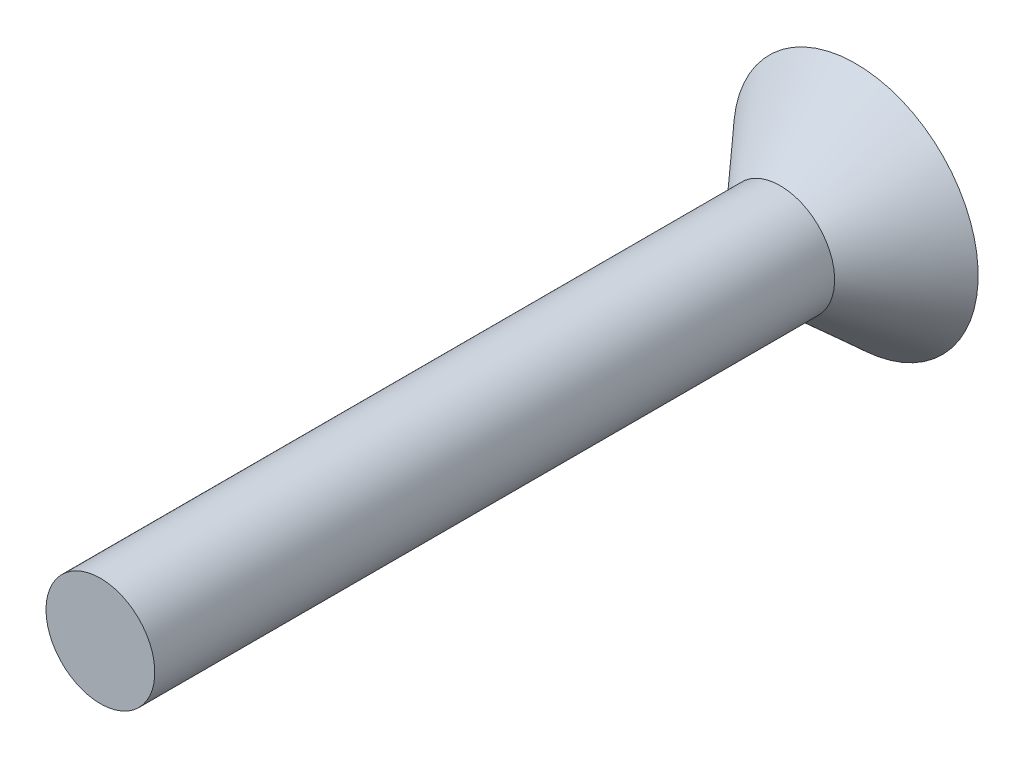
SolidWorks part; units mm, degrees
ref_plane "Front Plane" through (0, 0, 0) normal (0, 0, 1) x (1, 0, 0)
ref_plane "Top Plane" through (0, 0, 0) normal (0, 1, 0) x (1, 0, 0)
ref_plane "Right Plane" through (0, 0, 0) normal (1, 0, 0) x (0, 0, -1)
sketch "H1_SK_profile" plane through (0, 0, 0) normal (1, 0, 0) x (0, 0, -1)
  line L0 (11.43, 0) -> (11.43, 2.0574)
  line L1 (11.43, 2.0574) -> (10.16, 0.9144)
  line L2 (10.16, 0.9144) -> (-1.27, 0.9144)
  line L3 (-1.27, 0.9144) -> (-1.27, 0)
  line L4 (-1.27, 0) -> (11.43, 0)
  line L5 (15.24, 0) -> (-5.08, 0) construction
revolve "H1_Body" add sketch "H1_SK_profile" angle 360 about L5
ref_plane "Z_-0_4500" through (0, 0, -11.43) normal (0, 0, 1) x (1, 0, 0)
sketch "H1_SK_crossRecess" plane through (0, 0, -11.43) normal (0, 0, 1) x (1, 0, 0)
  line L0 (1.3462, -0.2159) -> (1.3462, 0.2159)
  line L1 (1.3462, 0.2159) -> (0.5969, 0.2159)
  line L2 (0.5969, 0.2159) -> (0.2159, 0.5969)
  line L3 (0.2159, 0.5969) -> (0.2159, 1.3462)
  line L4 (0.2159, 1.3462) -> (-0.2159, 1.3462)
  line L5 (-0.2159, 1.3462) -> (-0.2159, 0.5969)
  line L6 (-0.2159, 0.5969) -> (-0.5969, 0.2159)
  line L7 (-0.5969, 0.2159) -> (-1.3462, 0.2159)
  line L8 (-1.3462, 0.2159) -> (-1.3462, -0.2159)
  line L9 (-1.3462, -0.2159) -> (-0.5969, -0.2159)
  line L10 (-0.5969, -0.2159) -> (-0.2159, -0.5969)
  line L11 (-0.2159, -0.5969) -> (-0.2159, -1.3462)
  line L12 (-0.2159, -1.3462) -> (0.2159, -1.3462)
  line L13 (0.2159, -1.3462) -> (0.2159, -0.5969)
  line L14 (0.2159, -0.5969) -> (0.5969, -0.2159)
  line L15 (0.5969, -0.2159) -> (1.3462, -0.2159)
extrude "H1_CrossRecess_4deg" cut sketch "H1_SK_crossRecess" along normal blind 0.762 draft 4
